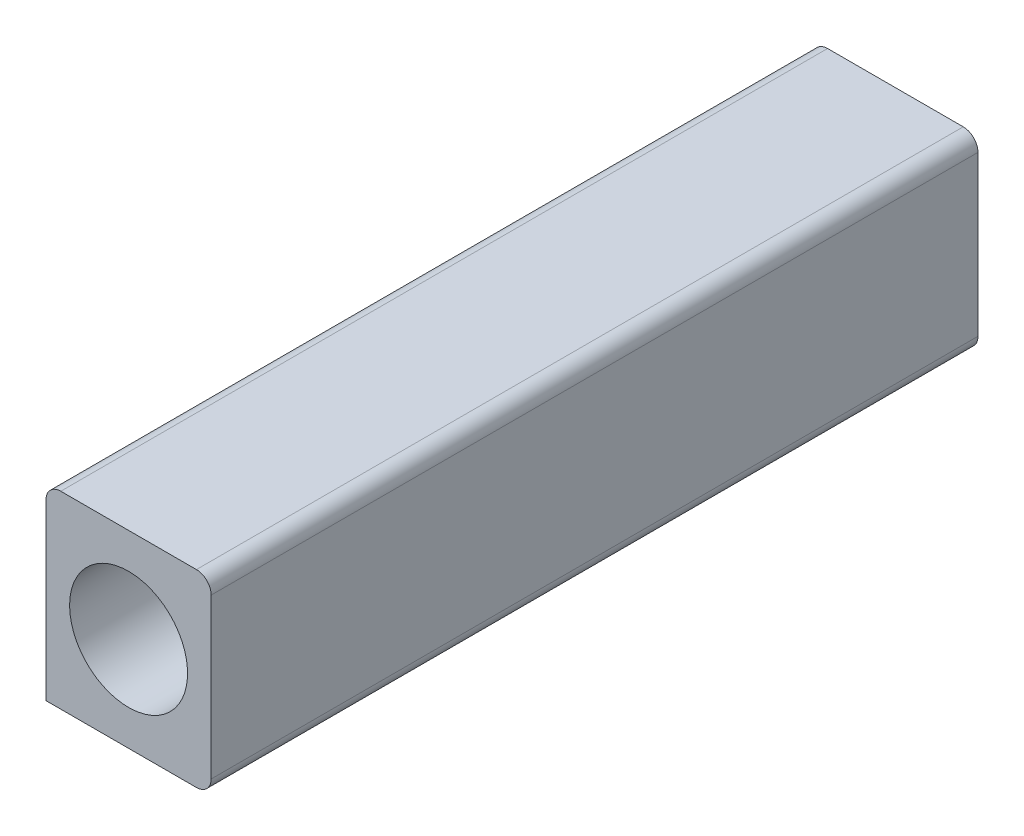
SolidWorks part; units mm, degrees
ref_plane "前视基准面" through (0, 0, 0) normal (0, 0, 1) x (1, 0, 0)
ref_plane "上视基准面" through (0, 0, 0) normal (0, 1, 0) x (1, 0, 0)
ref_plane "右视基准面" through (0, 0, 0) normal (1, 0, 0) x (0, 0, -1)
other "Configuration Table"
sketch "草图8" plane through (0, 0, 0) normal (0, 0, 1) x (1, 0, 0)
  line L0 (-28, -32) -> (28, -32)
  line L1 (28, -32) -> (28, 32)
  line L2 (28, 32) -> (-28, 32)
  line L3 (-28, 32) -> (-28, -32)
extrude "凸台-拉伸1" add sketch "草图8" along normal blind 260
sketch "草图9" plane through (0, 0, 0) normal (0, 0, -1) x (-1, 0, 0)
  circle A0 centre (0, 0) radius 20
extrude "切除-拉伸1" cut sketch "草图9" against normal through all
fillet "圆角1" radius 5 3 edges at (28, -32, 130) (-28, 32, 130) (28, 32, 130)
